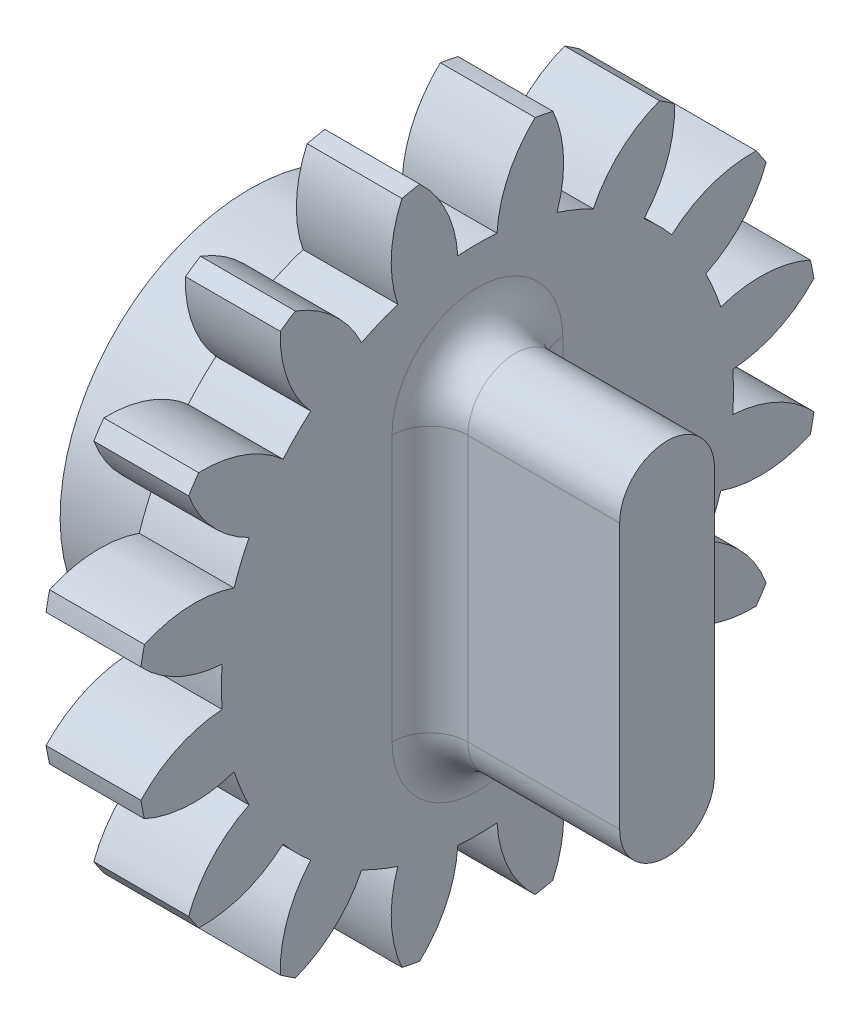
SolidWorks part; units mm, degrees
ref_plane "Plane1" through (0, 0, 0) normal (0, 0, 1) x (1, 0, 0)
ref_plane "Plane2" through (0, 0, 0) normal (0, 1, 0) x (1, 0, 0)
ref_plane "Plane3" through (0, 0, 0) normal (1, 0, 0) x (0, 0, -1)
other "Configuration Table"
sketch "HoldingSke" plane through (0, 0, 0) normal (0, 1, 0) x (1, 0, 0)
  line L0 (0, 0) -> (0.4806, -0.1378)
  line L1 (-15, 0) -> (100, 0) construction
  line L2 (0, 0) -> (-2.1039, 2.3779)
  line L3 (0, 0) -> (-11.863, 4.5341)
  line L4 (0, 0) -> (8.3015, 2.3804)
  line L5 (0, 0) -> (-46.8476, -17.4728)
  line L6 (0, 0) -> (-4.1448, -2.7965)
  line L7 (-2.1039, 2.3779) -> (8.6586, 51.2059)
  line L8 (-76.2, 54.61) -> (-75.3, 54.61)
  line L9 (-71.009, 38.7566) -> (-53.1078, 45.2721)
  line L10 (-76.2, 71.12) -> (104.1128, 71.12)
  line L11 (0, 0) -> (-5, 0)
  line L12 (-76.2, 101.6) -> (-76.133, 101.6)
  line L13 (24.9733, 27.94) -> (52.9518, 28.4284)
  line L14 (24.9733, 27.94) -> (24.9743, 27.94)
  line L15 (24.9733, 27.94) -> (100.4006, 29.5858)
  line L16 (-63.627, -2) -> (-12.827, -2)
  circle A0 centre (0, 0) radius 2.5
  circle A1 centre (0, 0) radius 13.499
  circle A2 centre (0, 0) radius 37.5
  circle A3 centre (0, 0) radius 2.5
  dimension "MHD" = 26.998
  dimension "Hub_dia" = 75
  dimension "Bore" = 5
  dimension "MBD" = 5
  dimension "Num_teeth" = 16
  dimension "Pitch" = 0.5
  dimension "Overall_len" = 50
  dimension "Show_teeth" = 16
  dimension "Thickness" = 5
  dimension "OAL" = 50.0001
  dimension "T_dim" = 0.9
  dimension "Ap" = 20
  dimension "H" = 19.05
  dimension "Pitch_radius" = 180.3128
  dimension "Width" = 5
  dimension "Backlash" = 0.067
  dimension "Addendum_fac" = 1
  dimension "Dedendum_fac" = 1.25
  dimension "Clearance_fac" = 0.25
  dimension "Dedendum_add" = 0.001
  dimension "Module" = 2
sketch "BasProSke" plane through (0, 0, 0) normal (0, 1, 0) x (1, 0, 0)
  line L0 (-10, 0) -> (60, 0) construction
  line L1 (0, 0) -> (0, 18)
  line L2 (0, 0) -> (5, 0)
  line L3 (5, 0) -> (5, 18)
  line L4 (5, 18) -> (0, 18)
  dimension "Thickness" = 5
  dimension "Diameter" = 36
revolve "Base-Revolve" add sketch "BasProSke" angle 360 about L0
sketch "TooCutSke" plane through (0, 0, 0) normal (1, 0, 0) x (0, 0, -1)
  line L1 (0, 0) -> (0, 107) construction
  line L2 (0, 0) -> (-1.6854, 15.911) construction
  line L3 (0, 0) -> (-6.2172, 31.2558) construction
  line L4 (-1.6854, 15.911) -> (-3.1086, 15.6279) construction
  arc A0 (1.0343, 13.4593) -> (-1.0343, 13.4593) centre (0, 0) ccw
  arc A1 (3.0657, 17.7628) -> (-3.0657, 17.7628) centre (0, 0) ccw
  circle A2 centre (0, 0) radius 16 construction
  circle A3 centre (0, 0) radius 15.0351 construction
  arc A4 (-1.0343, 13.4593) -> (-3.0657, 17.7628) centre (-7.4228, 13.075) ccw
  arc A5 (3.0657, 17.7628) -> (1.0343, 13.4593) centre (7.4228, 13.075) ccw
  dimension "Root_dia" = 26.998
  dimension "Overcut_dia" = 36.0508
  dimension "Pitch_dia" = 32
  dimension "Base_dia" = 30.0702
  dimension "Flank_rad" = 6.4
  dimension "Half_ang" = 11.25
  dimension "Half_CT" = 1.451
extrude "ToothCut" cut sketch "TooCutSke" along normal through all
fillet "Breaks" [suppressed] radius 0.04
fillet "RootFillets" [suppressed] radius 0.501
pattern_circular "TeethCuts" count 16 every 22.5 about axis through (-10, 0, 0) along (1, 0, 0) of "ToothCut", "RootFillets", "Breaks"
sketch "HubNeaOneSke" plane through (0, 0, 0) normal (-1, 0, 0) x (0, 0, 1)
  circle A0 centre (0, 0) radius 13.499
  dimension "Diameter" = 26.998
extrude "HubNearOne" [suppressed] add sketch "HubNeaOneSke" along normal blind 45.0001
sketch "HubNeaBotSke" plane through (0, 0, 0) normal (-1, 0, 0) x (0, 0, 1)
  circle A0 centre (0, 0) radius 13.499
  dimension "Diameter" = 26.998
extrude "HubNearBoth" [suppressed] add sketch "HubNeaBotSke" along normal blind 22.5
ref_plane "FarPln" through (5, 0, 0) normal (1, 0, 0) x (0, 0, -1)
sketch "HubFarSke" plane through (5, 0, 0) normal (1, 0, 0) x (0, 0, -1)
  circle A0 centre (0, 0) radius 13.499
  dimension "Diameter" = 26.998
extrude "HubFar" [suppressed] add sketch "HubFarSke" along normal blind 22.5
sketch "BorSke" plane through (0, 0, 0) normal (1, 0, 0) x (0, 0, -1)
  circle A0 centre (0, 0) radius 2.5
  dimension "Diameter" = 5
extrude "Bore" cut sketch "BorSke" along normal mid plane 100.0001
sketch "KeySke" plane through (0, 0, 0) normal (1, 0, 0) x (0, 0, -1)
  line L0 (-1, 0) -> (-1, 3.4)
  line L1 (-1, 3.4) -> (1, 3.4)
  line L2 (1, 3.4) -> (1, 0)
  line L3 (0, 0) -> (0, 34) construction
  line L4 (-1, 0) -> (1, 0)
  dimension "Offset" = 3.4
  dimension "Width" = 2
extrude "Keyway" [suppressed] cut sketch "KeySke" along normal mid plane 100.0001
pattern_circular "Keyway2" [suppressed] count 2 every 90 about axis through (-10, 0, 0) along (1, 0, 0)
sketch "Sketch1" plane through (0, 0, 0) normal (-1, 0, 0) x (0, 0, 1)
  circle A0 centre (0, 0) radius 10
  dimension "D1" = 20
extrude "Boss-Extrude1" add sketch "Sketch1" along normal blind 7 and the other way through all
sketch "Sketch2" plane through (-7, 0, 0) normal (-1, 0, 0) x (0, 0, 1)
  circle A0 centre (-9.0927, 4.1622) radius 1.25
  circle A1 centre (0, 0) radius 10 construction
  dimension "D1" = 2.5
extrude "Boss-Extrude3" add sketch "Sketch2" against normal blind 1.8 contours A0
sketch "Sketch3" plane through (5, 0, 0) normal (1, 0, 0) x (0, 0, -1)
  line L0 (0, 4.5) -> (0, -4.5) construction
  line L1 (2.5, 7) -> (2.5, -7)
  line L2 (-2.5, 7) -> (-2.5, -7)
  line L3 (0, 7) -> (0, 4.5) construction
  line L4 (0, -4.5) -> (0, -7) construction
  arc A0 (2.5, 7) -> (-2.5, 7) centre (0, 7) ccw
  arc A1 (-2.5, -7) -> (2.5, -7) centre (0, -7) ccw
  arc A2 (0, 4.5) -> (2.5, 7) centre (0, 7) ccw construction
  arc A3 (2.5, -7) -> (0, -4.5) centre (0, -7) ccw construction
  arc A4 (0, -4.5) -> (-2.5, -7) centre (0, -7) ccw construction
  arc A5 (-2.5, 7) -> (0, 4.5) centre (0, 7) ccw construction
  point P4 (0, 0)
  dimension "D1" = 5
  dimension "D2" = 7
  dimension "D3" = 7
extrude "Boss-Extrude4" add sketch "Sketch3" along normal blind 10
fillet "Fillet1" radius 2 4 edges at (5, -9.5, 0) (5, 0, 2.5) (5, 9.5, 0) (5, 0, -2.5)
equation "' \"Module@HoldingSke\" = 6.35"
equation "' \"Num_teeth@HoldingSke\" = 12"
equation "' \"Ap@HoldingSke\" =  20"
equation "' \"Ap@HoldingSke\" = 20"
equation "' \"Width@HoldingSke\" = 0.5 * 25.4"
equation "' \"Hub_dia@HoldingSke\"= 1 * 25.4"
equation "' \"Hub_dia@HoldingSke\" = 1 * 25.4"
equation "' \"Overall_len@HoldingSke\" = 1.0 * 25.4"
equation "' \"Bore@HoldingSke\" = 0.75 * 25.4"
equation "' \"T_dim@HoldingSke\" = 0.1 * 25.4"
equation "' \"Width@KeySke\" = 0.25 * 25.4"
equation "' \"Show_teeth@HoldingSke\" = 13"
equation "' \"Backlash@HoldingSke\" = 0.009 * 25.4"
equation "' \"Addendum_fac@HoldingSke\" = 1.0"
equation "' \"Dedendum_fac@HoldingSke\" = 1.25"
equation "' \"Dedendum_add@HoldingSke\" = 0.00005 * 25.4"
equation "' \"Clearance_fac@HoldingSke\" = 0.25"
equation "\"Pitch@HoldingSke\" = 1 / \"Module@HoldingSke\""
equation "\"Overcut_dia@TooCutSke\" = (\"Num_teeth@HoldingSke\" + 2 * \"Addendum_fac@HoldingSke\") / \"Pitch@HoldingSke\" + 0.002 * 25.4"
equation "\"Pitch_dia@TooCutSke\" = \"Num_teeth@HoldingSke\" / \"Pitch@HoldingSke\""
equation "\"Base_dia@TooCutSke\" = \"Num_teeth@HoldingSke\" / \"Pitch@HoldingSke\" * cos((\"Ap@HoldingSke\"  * 3.14159265 / 180))"
equation "\"Root_dia@TooCutSke\" = (\"Num_teeth@HoldingSke\" + 2) / \"Pitch@HoldingSke\" - 2 * (\"Addendum_fac@HoldingSke\" + \"Dedendum_fac@HoldingSke\") / \"Pitch@HoldingSke\" - \"Dedendum_add@HoldingSke\" * 2"
equation "\"Half_ang@TooCutSke\" = 180 / \"Num_teeth@HoldingSke\""
equation "\"Half_CT@TooCutSke\" = \"Num_teeth@HoldingSke\" / \"Pitch@HoldingSke\" * sin((3.14159265 / 2 / \"Num_teeth@HoldingSke\")) / 2 - 7 * \"Backlash@HoldingSke\" / 4"
equation "\"Flank_rad@TooCutSke\" = \"Num_teeth@HoldingSke\" / \"Pitch@HoldingSke\" / 5"
equation "\"Radius@RootFillets\" = \"Clearance_fac@HoldingSke\" / \"Pitch@HoldingSke\" + \"Dedendum_add@HoldingSke\""
equation "\"Break_rad@Breaks\" = 0.02 / \"Pitch@HoldingSke\""
equation "\"Thickness@HoldingSke\" = \"Width@HoldingSke\""
equation "\"OAL@HoldingSke\" = \"Thickness@HoldingSke\""
equation "\"MHD@HoldingSke\" = (\"Num_teeth@HoldingSke\" + 2) / \"Pitch@HoldingSke\" - 2 * (\"Addendum_fac@HoldingSke\" + \"Dedendum_fac@HoldingSke\")  / \"Pitch@HoldingSke\" - \"Dedendum_add@HoldingSke\" * 2"
equation "\"MBD@HoldingSke\" = (\"Num_teeth@HoldingSke\" + 2) / \"Pitch@HoldingSke\" - 2 * (\"Addendum_fac@HoldingSke\" + \"Dedendum_fac@HoldingSke\")  / \"Pitch@HoldingSke\" - \"Dedendum_add@HoldingSke\" * 2 - 0.002 * 25.4"
equation "\"MHD@HoldingSke\" = ((sgn( \"MHD@HoldingSke\" - \"Hub_dia@HoldingSke\" )-1)*( \"MHD@HoldingSke\" - \"Hub_dia@HoldingSke\" ))/-2+ \"Hub_dia@HoldingSke\""
equation "\"MBD@HoldingSke\" = ((sgn( \"MBD@HoldingSke\" - \"Bore@HoldingSke\" )-1)*( \"MBD@HoldingSke\" - \"Bore@HoldingSke\" ))/-2+ \"Bore@HoldingSke\""
equation "\"OAL@HoldingSke\" = ((sgn( \"OAL@HoldingSke\" - \"Overall_len@HoldingSke\" )+1)*( \"OAL@HoldingSke\" - \"Overall_len@HoldingSke\" ))/2 + \"Overall_len@HoldingSke\" + 0.000002 * 25.4"
equation "\"Num_teeth@TeethCuts\" = int( \"Show_teeth@HoldingSke\" ) + 1"
equation "\"Num_teeth@TeethCuts\" = ((sgn( \"Num_teeth@TeethCuts\" - \"Num_teeth@HoldingSke\" )-1)*( \"Num_teeth@TeethCuts\" - \"Num_teeth@HoldingSke\" ))/-2+ \"Num_teeth@HoldingSke\""
equation "\"Num_teeth@TeethCuts\" = ((sgn( \"Num_teeth@TeethCuts\" - 2.0)+1)*( \"Num_teeth@TeethCuts\" - 2.0))/2 +2.0"
equation "\"Angle@TeethCuts\" = 360.0 / \"Num_teeth@HoldingSke\""
equation "\"Diameter@BasProSke\" = (\"Num_teeth@HoldingSke\" + 2 * \"Addendum_fac@HoldingSke\") / \"Pitch@HoldingSke\""
equation "\"Thickness@BasProSke\"  = \"Thickness@HoldingSke\""
equation "' \"Fillet_rad@BasProSke\" =  \"Thickness@HoldingSke\" * 0.05"
equation "' \"Fillet_rad@BasProSke\" = \"Thickness@HoldingSke\" * 0.05"
equation "\"MHD@HoldingSke\" = ((sgn( \"MHD@HoldingSke\" - \"Root_dia@TooCutSke\" )-1)*( \"MHD@HoldingSke\" - \"Root_dia@TooCutSke\" ))/-2+ \"Root_dia@TooCutSke\""
equation "\"Diameter@HubNeaOneSke\" = \"MHD@HoldingSke\""
equation "\"Length@HubNearOne\" = \"OAL@HoldingSke\" - \"Thickness@BasProSke\""
equation "\"Diameter@HubNeaBotSke\" = \"MHD@HoldingSke\""
equation "\"Length@HubNearBoth\" = ( \"OAL@HoldingSke\" - \"Thickness@BasProSke\" ) / 2.0"
equation "\"Thickness@FarPln\" = \"Thickness@BasProSke\""
equation "\"Diameter@HubFarSke\" = \"MHD@HoldingSke\""
equation "\"Length@HubFar\" = ( \"OAL@HoldingSke\" - \"Thickness@BasProSke\" ) / 2.0"
equation "\"Diameter@BorSke\" = \"MBD@HoldingSke\""
equation "\"D1@Bore\" = \"OAL@HoldingSke\" * 2.0"
equation "\"D1@Keyway\" = \"OAL@HoldingSke\" * 2.0"
equation "\"Offset@KeySke\" = \"T_dim@HoldingSke\" + \"MBD@HoldingSke\" / 2.0"
